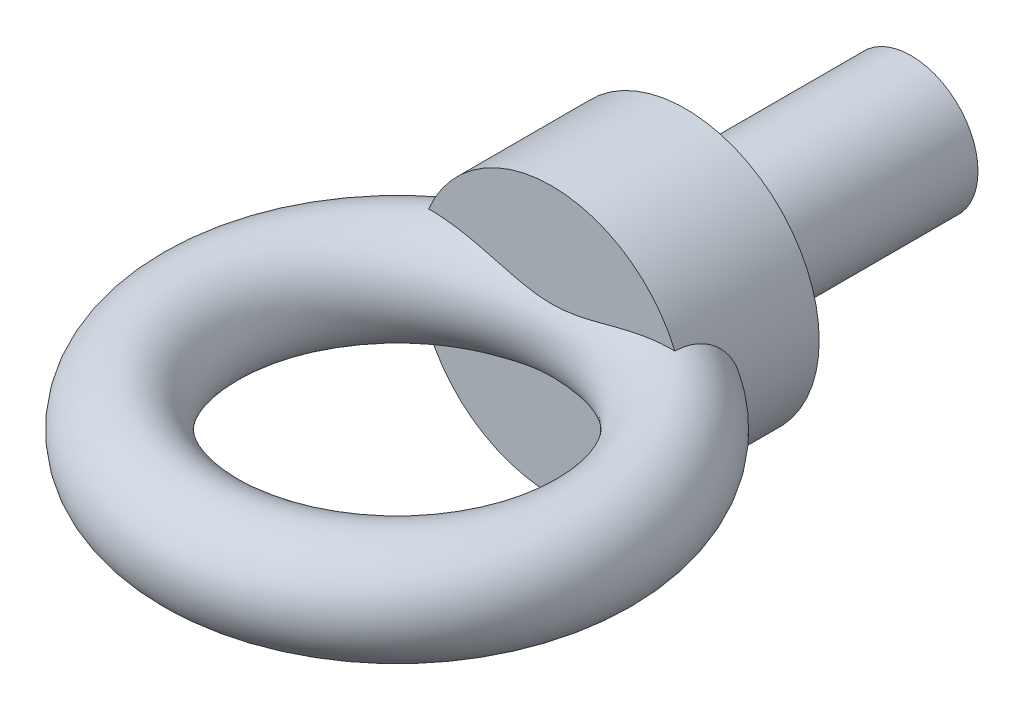
SolidWorks part; units mm, degrees
ref_plane "正面" through (0, 0, 0) normal (0, 0, 1) x (1, 0, 0)
ref_plane "平面" through (0, 0, 0) normal (0, 1, 0) x (1, 0, 0)
ref_plane "右側面" through (0, 0, 0) normal (1, 0, 0) x (0, 0, -1)
sketch "ｽｹｯﾁ1" plane through (0, 0, 0) normal (0, 0, 1) x (1, 0, 0)
  circle A0 centre (0, 0) radius 8
  dimension "D1" = 16
extrude "ﾎﾞｽ - 押し出し1" add sketch "ｽｹｯﾁ1" along normal blind 38
cosmetic thread "ねじ山1" parameters "D2"=15
sketch "ｽｹｯﾁ3" plane through (0, 0, 0) normal (0, 1, 0) x (1, 0, 0)
  line L0 (-8, -38) -> (8, -38) construction
  line L1 (-8, -38) -> (8, -38)
  circle A0 centre (0, -61.4967) radius 23.4967
sketch "ｽｹｯﾁ4" plane through (0, 0, 0) normal (1, 0, 0) x (0, 0, -1)
  line L0 (-38, 8) -> (-38, -8) construction
  line L1 (-38, 8) -> (-38, -8)
  circle A0 centre (-38, 0) radius 6.25
  dimension "D1" = 12.5
ref_plane "平面1" through (0, 0, 27) normal (0, 0, -1) x (-1, 0, 0)
sweep "ｽｲｰﾌﾟ1" add profiles "ｽｹｯﾁ4" path "ｽｹｯﾁ3"
sketch "ｽｹｯﾁ5" plane through (0, 0, 27) normal (0, 0, -1) x (-1, 0, 0)
  circle A0 centre (0, 0) radius 16
  dimension "D1" = 32
extrude "ﾎﾞｽ - 押し出し2" add sketch "ｽｹｯﾁ5" against normal blind 16
